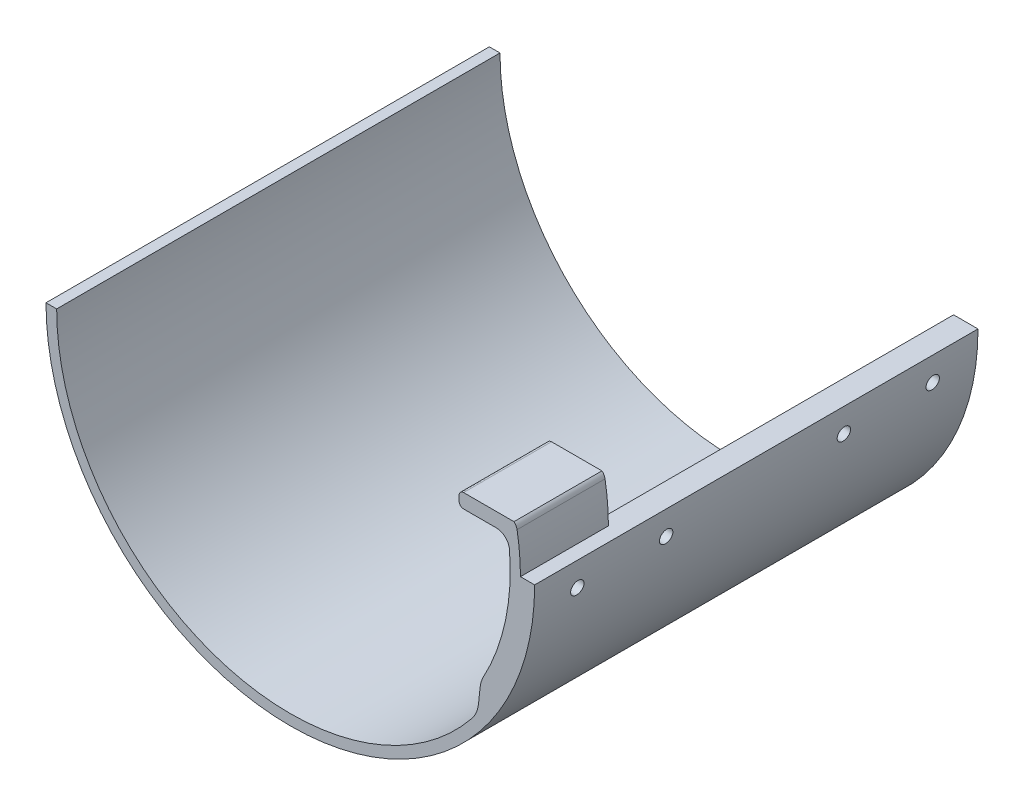
SolidWorks part; units mm, degrees
ref_plane "前视基准面" through (0, 0, 0) normal (0, 0, 1) x (1, 0, 0)
ref_plane "上视基准面" through (0, 0, 0) normal (0, 1, 0) x (1, 0, 0)
ref_plane "右视基准面" through (0, 0, 0) normal (1, 0, 0) x (0, 0, -1)
other "Configuration Table"
sketch "草图1" plane through (0, 0, 0) normal (0, 0, 1) x (1, 0, 0)
  line L0 (-55, 0) -> (-52.6, 0)
  line L1 (51.8, 0) -> (55, 0)
  line L2 (-52.6, 0) -> (51.8, 0) construction
  line L5 (42.7014, -26.2251) -> (42.3718, -29.4462)
  line L6 (0, 0) -> (0, 10) construction
  line L7 (0, 10) -> (39, 10) construction
  line L9 (38, 9) -> (38, 7.8)
  line L10 (39, 6.8) -> (46.3445, 6.8)
  line L11 (39, 10) -> (50.344, 10)
  arc A0 (-55, 0) -> (55, 0) centre (0, 0) ccw
  arc A1 (-52.6, 0) -> (40.8436, -33.1445) centre (0, 0) ccw
  arc A2 (51.0485, 8.7916) -> (51.8, 0) centre (0, 0) cw
  arc A3 (43.5118, -23.6002) -> (49.3344, 4.0452) centre (0, 0) ccw
  arc A4 (42.3718, -29.4462) -> (40.8436, -33.1445) centre (35.4082, -28.7336) cw
  arc A5 (42.7014, -26.2251) -> (43.5118, -23.6002) centre (49.665, -26.9376) cw
  arc A6 (49.3344, 4.0452) -> (46.3445, 6.8) centre (46.3445, 3.8) ccw
  arc A7 (51.0485, 8.7916) -> (50.344, 10) centre (49.0775, 8.4521) ccw
  arc A8 (39, 6.8) -> (38, 7.8) centre (39, 7.8) cw
  arc A9 (38, 9) -> (39, 10) centre (39, 9) cw
  point P16 (42.8489, -24.7835)
  point P25 (52.0183, 10)
  point P28 (38, 6.8)
  point P31 (30.5845, 10)
  dimension "D1" = 110
  dimension "D2" = 105.2
  dimension "D3" = 99
  dimension "D6" = 7
  dimension "D9" = 3
  dimension "D10" = 2
  dimension "D11" = 1
  dimension "D12" = 1
  dimension "D14" = 51.8
  dimension "D5" = 39
  dimension "D7" = 3.2
  dimension "D8" = 21.4339
  dimension "D13" = 10
extrude "凸台-拉伸1" add sketch "草图1" along normal blind 99.8
sketch "草图4" plane through (0, 0, 99.8) normal (0, 0, 1) x (1, 0, 0)
  line L0 (55, 0) -> (0, 0)
  line L1 (0, 0) -> (50.017, 22.8758)
  arc A0 (55, 0) -> (50.017, 22.8758) centre (0, 0) ccw
sketch "草图5" plane through (0, 0, 0) normal (0, 0, -1) x (-1, 0, 0)
  line L0 (0, 0) -> (0, -5.5)
  line L1 (0, -5.5) -> (54.3615, -5.5)
  line L2 (0, 0) -> (54.3615, -5.5) construction
  line L3 (0, 0) -> (5.5, 54.3615) construction
  line L4 (0, 0) -> (0, 54.639) construction
  line L5 (0, 0) -> (-54.3615, -5.5) construction
  line L6 (0, 0) -> (-5.5, 54.3615) construction
  circle A0 centre (0, 0) radius 54.639
  dimension "D1" = 5.5
  dimension "D2" = 90
ref_plane "基准面1" through (0, 0, 0) normal (-0.9949, 0.1007, 0) x (0.1007, 0.9949, 0)
sketch "草图7" plane through (0, 0, 0) normal (-0.9949, 0.1007, 0) x (0.1007, 0.9949, 0)
  line L0 (-5.5363, -99.8) -> (-5.5363, 0) construction
  line L1 (-55, -99.8) -> (5.5363, -99.8) construction
  line L2 (-0.1363, 0) -> (-0.1363, -99.8) construction
  line L3 (54.639, 0) -> (-54.639, 0) construction
  line L4 (-5.4721, 0) -> (-10.9441, 0) construction
  circle A0 centre (-0.1363, -9.9) radius 1.5
  circle A1 centre (-0.1363, -29.9) radius 1.5
  circle A2 centre (-0.1363, -69.9) radius 1.5
  circle A3 centre (-0.1363, -89.9) radius 1.5
  dimension "D1" = 3
  dimension "D2" = 3
  dimension "D3" = 3
  dimension "D4" = 3
  dimension "D5" = 5.4
  dimension "D6" = 9.9
  dimension "D7" = 20
  dimension "D8" = 9.9
  dimension "D9" = 20
extrude "切除-拉伸6" cut sketch "草图7" against normal blind 80
sketch "草图8" plane through (0, 0, 0) normal (0, 0, -1) x (-1, 0, 0)
  line L0 (-55, 0) -> (0, 0) construction
  line L1 (-50.017, 22.8758) -> (0, 0)
  line L2 (0, 0) -> (-55, 0)
  arc A0 (-50.017, 22.8758) -> (-55, 0) centre (0, 0) ccw
extrude "切除-拉伸7" cut sketch "草图8" against normal blind 80
